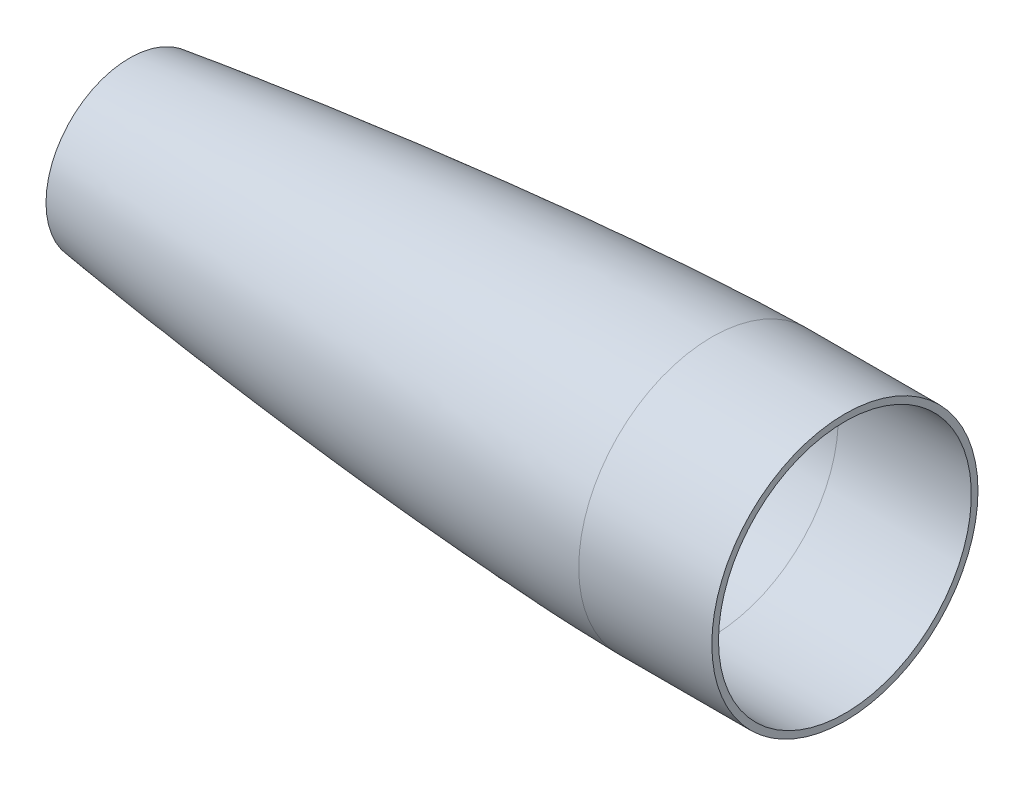
SolidWorks part; units mm, degrees
ref_plane "Front Plane" through (0, 0, 0) normal (0, 0, 1) x (1, 0, 0)
ref_plane "Top Plane" through (0, 0, 0) normal (0, 1, 0) x (1, 0, 0)
ref_plane "Right Plane" through (0, 0, 0) normal (1, 0, 0) x (0, 0, -1)
curve "Curve1"
  spline degree 3 poles (0, 0, 0) (0.3239, 0.2563, 0) (0.9404, 0.7441, 0) (1.9928, 1.2129, 0) (2.9928, 1.6503, 0) (3.9962, 2.0429, 0) (4.997, 2.4136, 0) (5.9977, 2.765, 0) (6.9982, 3.102, 0) (7.9985, 3.4266, 0) (8.9987, 3.7409, 0) (9.9989, 4.0463, 0) (10.999, 4.3437, 0) (11.9992, 4.6341, 0) (12.9993, 4.9182, 0) (13.9993, 5.1965, 0) (14.9994, 5.4695, 0) (15.9994, 5.7378, 0) (16.9995, 6.0015, 0) (17.9995, 6.261, 0) (18.9996, 6.5167, 0) (19.9996, 6.7687, 0) (20.9996, 7.0173, 0) (21.9996, 7.2626, 0) (22.9997, 7.5048, 0) (23.9997, 7.7441, 0) (24.9997, 7.9806, 0) (25.9997, 8.2145, 0) (26.9997, 8.4458, 0) (27.9997, 8.6747, 0) (28.9998, 8.9012, 0) (29.9998, 9.1256, 0) (30.9998, 9.3477, 0) (31.9998, 9.5678, 0) (32.9998, 9.7859, 0) (33.9998, 10.0021, 0) (34.9998, 10.2164, 0) (35.9998, 10.4289, 0) (36.9998, 10.6396, 0) (37.9998, 10.8486, 0) (38.9998, 11.056, 0) (39.9998, 11.2617, 0) (40.9999, 11.4659, 0) (41.9999, 11.6686, 0) (42.9999, 11.8698, 0) (43.9999, 12.0696, 0) (44.9999, 12.2679, 0) (45.9999, 12.4649, 0) (46.9999, 12.6605, 0) (47.9999, 12.8548, 0) (48.9999, 13.0478, 0) (49.9999, 13.2396, 0) (50.9999, 13.4301, 0) (51.9999, 13.6194, 0) (52.9999, 13.8076, 0) (53.9999, 13.9946, 0) (54.9999, 14.1804, 0) (55.9999, 14.3652, 0) (56.9999, 14.5488, 0) (57.9999, 14.7314, 0) (58.9999, 14.9129, 0) (59.9999, 15.0934, 0) (60.9999, 15.2728, 0) (61.9999, 15.4513, 0) (62.9999, 15.6288, 0) (63.9999, 15.8052, 0) (64.9999, 15.9808, 0) (65.9999, 16.1554, 0) (66.9999, 16.329, 0) (67.9999, 16.5018, 0) (68.9999, 16.6736, 0) (69.9999, 16.8445, 0) (70.9999, 17.0146, 0) (71.9999, 17.1838, 0) (72.9999, 17.3522, 0) (73.9999, 17.5197, 0) (74.9999, 17.6863, 0) (75.9999, 17.8522, 0) (76.9999, 18.0172, 0) (77.9999, 18.1814, 0) (78.9999, 18.3449, 0) (79.9999, 18.5075, 0) (80.9999, 18.6694, 0) (81.9999, 18.8305, 0) (82.9999, 18.9908, 0) (83.9999, 19.1504, 0) (84.9999, 19.3092, 0) (85.9999, 19.4673, 0) (86.9999, 19.6247, 0) (87.9999, 19.7814, 0) (88.9999, 19.9373, 0) (89.9999, 20.0925, 0) (90.9999, 20.2471, 0) (91.9999, 20.4009, 0) (92.9999, 20.554, 0) (93.9999, 20.7065, 0) (95, 20.8583, 0) (96, 21.0094, 0) (97, 21.1598, 0) (98, 21.3096, 0) (99, 21.4587, 0) (100, 21.6072, 0) (101, 21.755, 0) (102, 21.9022, 0) (103, 22.0488, 0) (104, 22.1947, 0) (105, 22.34, 0) (106, 22.4846, 0) (107, 22.6287, 0) (108, 22.7721, 0) (109, 22.915, 0) (110, 23.0572, 0) (111, 23.1988, 0) (112, 23.3398, 0) (113, 23.4803, 0) (114, 23.6201, 0) (115, 23.7594, 0) (116, 23.898, 0) (117, 24.0361, 0) (118, 24.1736, 0) (119, 24.3106, 0) (120, 24.4469, 0) (121, 24.5827, 0) (122, 24.718, 0) (123, 24.8526, 0) (124, 24.9867, 0) (125, 25.1203, 0) (126, 25.2533, 0) (127, 25.3857, 0) (128, 25.5176, 0) (129, 25.649, 0) (130, 25.7798, 0) (131, 25.91, 0) (132, 26.0397, 0) (133, 26.1689, 0) (134, 26.2975, 0) (135, 26.4257, 0) (136, 26.5532, 0) (137, 26.6803, 0) (138, 26.8068, 0) (139, 26.9328, 0) (140, 27.0582, 0) (141, 27.1832, 0) (142, 27.3076, 0) (143, 27.4315, 0) (144, 27.5549, 0) (145, 27.6777, 0) (146, 27.8001, 0) (147, 27.9219, 0) (148, 28.0432, 0) (149, 28.1641, 0) (150, 28.2844, 0) (151, 28.4041, 0) (152, 28.5234, 0) (153, 28.6422, 0) (154, 28.7605, 0) (155, 28.8782, 0) (156, 28.9955, 0) (157, 29.1122, 0) (158, 29.2285, 0) (159, 29.3442, 0) (160, 29.4595, 0) (161, 29.5742, 0) (162, 29.6885, 0) (163, 29.8022, 0) (164, 29.9155, 0) (165, 30.0282, 0) (166, 30.1405, 0) (167, 30.2522, 0) (168, 30.3635, 0) (169, 30.4743, 0) (170, 30.5845, 0) (171, 30.6943, 0) (172, 30.8036, 0) (173, 30.9124, 0) (174, 31.0207, 0) (175, 31.1285, 0) (176, 31.2358, 0) (177, 31.3426, 0) (178, 31.4489, 0) (179, 31.5547, 0) (180, 31.66, 0) (181, 31.7649, 0) (182, 31.8692, 0) (183, 31.973, 0) (184, 32.0764, 0) (185, 32.1792, 0) (186, 32.2816, 0) (187, 32.3834, 0) (188, 32.4848, 0) (189, 32.5856, 0) (190, 32.686, 0) (191, 32.7859, 0) (192, 32.8852, 0) (193, 32.9841, 0) (194, 33.0825, 0) (195, 33.1803, 0) (196, 33.2777, 0) (197, 33.3746, 0) (198, 33.4709, 0) (199, 33.5668, 0) (200, 33.6621, 0) (201, 33.757, 0) (202, 33.8513, 0) (203, 33.9451, 0) (204, 34.0385, 0) (205, 34.1313, 0) (206, 34.2236, 0) (207, 34.3153, 0) (208, 34.4066, 0) (209, 34.4973, 0) (210, 34.5876, 0) (211, 34.6773, 0) (212, 34.7665, 0) (213, 34.8551, 0) (214, 34.9433, 0) (215, 35.0309, 0) (216, 35.118, 0) (217, 35.2045, 0) (218, 35.2906, 0) (219, 35.3761, 0) (220, 35.461, 0) (221, 35.5454, 0) (222, 35.6293, 0) (223, 35.7126, 0) (224, 35.7954, 0) (225, 35.8776, 0) (226, 35.9593, 0) (227, 36.0404, 0) (228, 36.121, 0) (229, 36.201, 0) (230, 36.2805, 0) (231, 36.3594, 0) (232, 36.4377, 0) (233, 36.5154, 0) (234, 36.5926, 0) (235, 36.6692, 0) (236, 36.7452, 0) (237, 36.8206, 0) (238, 36.8954, 0) (239, 36.9696, 0) (240, 37.0432, 0) (241, 37.1163, 0) (242, 37.1887, 0) (243, 37.2605, 0) (244, 37.3317, 0) (245, 37.4022, 0) (246, 37.4722, 0) (247, 37.5415, 0) (248, 37.6102, 0) (249, 37.6782, 0) (250, 37.7455, 0) (251, 37.8123, 0) (252, 37.8783, 0) (253, 37.9437, 0) (254, 38.0084, 0) (255, 38.0725, 0) (256, 38.1358, 0) (257, 38.1985, 0) (258, 38.2604, 0) (259, 38.3216, 0) (260, 38.3821, 0) (261, 38.4419, 0) (262, 38.5009, 0) (263, 38.5592, 0) (264, 38.6168, 0) (265, 38.6735, 0) (266, 38.7295, 0) (267, 38.7847, 0) (268, 38.8391, 0) (269, 38.8926, 0) (270, 38.9454, 0) (271, 38.9972, 0) (272, 39.0483, 0) (273, 39.0984, 0) (274, 39.1477, 0) (275, 39.196, 0) (276, 39.2434, 0) (277, 39.2899, 0) (278, 39.3354, 0) (279, 39.3799, 0) (280, 39.4234, 0) (281, 39.4658, 0) (282, 39.5072, 0) (283, 39.5475, 0) (284, 39.5866, 0) (285, 39.6246, 0) (286, 39.6613, 0) (287, 39.6968, 0) (288, 39.731, 0) (289, 39.7638, 0) (290, 39.7952, 0) (291, 39.8251, 0) (292, 39.8533, 0) (293, 39.88, 0) (294, 39.9048, 0) (295, 39.9276, 0) (296, 39.9483, 0) (297, 39.9666, 0) (298, 39.982, 0) (299, 39.9947, 0) (299.6667, 39.9982, 0) (300, 40, 0) knots 0 0 0 0 0.004064 0.007736 0.011323 0.014865 0.018378 0.021871 0.025347 0.028811 0.032264 0.035709 0.039146 0.042576 0.046001 0.04942 0.052835 0.056246 0.059653 0.063056 0.066457 0.069854 0.073248 0.07664 0.08003 0.083417 0.086802 0.090186 0.093567 0.096946 0.100324 0.1037 0.107075 0.110448 0.11382 0.11719 0.120559 0.123927 0.127294 0.130659 0.134023 0.137387 0.140749 0.14411 0.14747 0.15083 0.154188 0.157546 0.160902 0.164258 0.167613 0.170968 0.174321 0.177674 0.181026 0.184378 0.187728 0.191078 0.194428 0.197776 0.201124 0.204472 0.207819 0.211165 0.214511 0.217856 0.221201 0.224545 0.227888 0.231231 0.234574 0.237916 0.241258 0.244599 0.247939 0.251279 0.254619 0.257958 0.261297 0.264636 0.267974 0.271311 0.274648 0.277985 0.281321 0.284657 0.287993 0.291328 0.294663 0.297997 0.301331 0.304665 0.307999 0.311332 0.314664 0.317997 0.321329 0.32466 0.327992 0.331323 0.334653 0.337984 0.341314 0.344643 0.347973 0.351302 0.354631 0.35796 0.361288 0.364616 0.367943 0.371271 0.374598 0.377925 0.381251 0.384578 0.387904 0.39123 0.394555 0.39788 0.401205 0.40453 0.407855 0.411179 0.414503 0.417827 0.42115 0.424474 0.427797 0.431119 0.434442 0.437764 0.441086 0.444408 0.44773 0.451051 0.454372 0.457693 0.461014 0.464335 0.467655 0.470975 0.474295 0.477615 0.480934 0.484253 0.487572 0.490891 0.49421 0.497528 0.500846 0.504165 0.507482 0.5108 0.514117 0.517435 0.520752 0.524068 0.527385 0.530702 0.534018 0.537334 0.54065 0.543965 0.547281 0.550596 0.553911 0.557226 0.560541 0.563856 0.56717 0.570484 0.573799 0.577112 0.580426 0.58374 0.587053 0.590366 0.593679 0.596992 0.600305 0.603617 0.606929 0.610242 0.613554 0.616865 0.620177 0.623489 0.6268 0.630111 0.633422 0.636733 0.640043 0.643354 0.646664 0.649974 0.653284 0.656594 0.659904 0.663213 0.666523 0.669832 0.673141 0.67645 0.679759 0.683067 0.686376 0.689684 0.692992 0.6963 0.699608 0.702916 0.706223 0.70953 0.712838 0.716145 0.719452 0.722758 0.726065 0.729371 0.732678 0.735984 0.73929 0.742596 0.745901 0.749207 0.752512 0.755817 0.759122 0.762427 0.765732 0.769037 0.772341 0.775646 0.77895 0.782254 0.785558 0.788862 0.792165 0.795469 0.798772 0.802075 0.805378 0.808681 0.811984 0.815287 0.818589 0.821891 0.825193 0.828496 0.831797 0.835099 0.838401 0.841702 0.845003 0.848305 0.851606 0.854907 0.858207 0.861508 0.864808 0.868109 0.871409 0.874709 0.878009 0.881308 0.884608 0.887907 0.891207 0.894506 0.897805 0.901104 0.904402 0.907701 0.910999 0.914297 0.917596 0.920894 0.924191 0.927489 0.930787 0.934084 0.937381 0.940678 0.943975 0.947272 0.950569 0.953865 0.957161 0.960458 0.963754 0.96705 0.970345 0.973641 0.976936 0.980232 0.983527 0.986822 0.990117 0.993411 0.996706 1 1 1 1
sketch "Sketch2" plane through (0, 0, 0) normal (0, 0, 1) x (1, 0, 0)
  line L0 (0, 0) -> (129.646, 0) construction
  line L2 (300, 40) -> (300.0106, 38) construction
  line L3 (0, 0) -> (4.2671, 0)
  line L4 (300, 40) -> (340, 40)
  line L5 (340, 40) -> (340, 38)
  line L6 (340, 38) -> (300.0106, 38)
  line L7 (125, 25.1202) -> (125, 0)
  line L8 (125, 0) -> (127, 0)
  line L9 (127, 0) -> (127, 23.3682)
  spline S0 degree 3 poles (-1605.8079, 2533.2499) (16.7759, -86.5021) (-13.4623, -5.6713) (1.9928, 1.2129) (2.9928, 1.6503) (3.9962, 2.0429) (4.997, 2.4136) (5.9977, 2.765) (6.9982, 3.102) (7.9985, 3.4266) (8.9987, 3.7409) (9.9989, 4.0463) (10.999, 4.3437) (11.9992, 4.6341) (12.9993, 4.9182) (13.9993, 5.1965) (14.9994, 5.4695) (15.9994, 5.7378) (17.3322, 6.0892) (18.9983, 6.5182) (20.9985, 7.0186) (22.9987, 7.506) (24.9988, 7.9817) (26.9989, 8.4468) (28.999, 8.9022) (31.332, 9.4229) (33.9983, 10.0043) (36.9985, 10.6416) (39.9986, 11.2636) (42.9987, 11.8715) (46.3318, 12.5325) (49.9982, 13.2423) (53.9984, 13.9971) (57.9985, 14.7338) (62.3316, 15.5134) (66.9981, 16.3324) (71.9982, 17.187) (77.3314, 18.0757) (82.9979, 18.9949) (88.9981, 19.9411) (95.3312, 20.913) (101.9978, 21.907) (108.9979, 22.9195) (116.3311, 23.9492) (123.9977, 24.9923) (131.9978, 26.0451) (140.331, 27.1059) (148.9975, 28.1706) (157.9977, 29.2349) (166.9978, 30.2586) (175.9979, 31.2421) (184.998, 32.1856) (193.998, 33.089) (202.665, 33.9198) (210.9985, 34.6826) (218.6654, 35.3525) (225.9989, 35.9637) (232.9989, 36.5199) (239.6657, 37.0229) (245.9992, 37.4758) (251.666, 37.8596) (256.9995, 38.2012) (261.6662, 38.4837) (265.9996, 38.7315) (269.9996, 38.9474) (273.6664, 39.1331) (276.9998, 39.2912) (279.9998, 39.4248) (282.6665, 39.5352) (284.9999, 39.6252) (286.9999, 39.6975) (288.9999, 39.7645) (290.6666, 39.8156) (292.3333, 39.8628) (293.6666, 39.8971) (295, 39.9276) (296, 39.9483) (297, 39.9666) (298, 39.982) (343.7491, 40.5639) (389.362, 18.16) (408.5654, 3036.1615) knots -0.154953 -0.154953 -0.154953 -0.154953 0.004064 0.007736 0.011323 0.014865 0.018378 0.021871 0.025347 0.028811 0.032264 0.035709 0.039146 0.042576 0.046001 0.04942 0.052835 0.056246 0.059653 0.066457 0.073248 0.08003 0.086802 0.093567 0.100324 0.107075 0.11719 0.127294 0.137387 0.14747 0.157546 0.170968 0.184378 0.197776 0.211165 0.227888 0.244599 0.261297 0.281321 0.301331 0.321329 0.344643 0.367943 0.39123 0.417827 0.444408 0.470975 0.500846 0.530702 0.560541 0.590366 0.620177 0.649974 0.679759 0.706223 0.732678 0.755817 0.77895 0.802075 0.821891 0.841702 0.858207 0.874709 0.887907 0.901104 0.914297 0.924191 0.934084 0.943975 0.950569 0.957161 0.963754 0.970345 0.973641 0.980232 0.983527 0.986822 0.990117 0.993411 0.996706 1.44228 1.44228 1.44228 1.44228 only from (0, 0) to (300, 40) construction
  spline S1 degree 3 poles (0, 0) (0.3239, 0.2563) (0.9404, 0.7441) (1.9928, 1.2129) (2.9928, 1.6503) (3.9962, 2.0429) (4.997, 2.4136) (5.9977, 2.765) (6.9982, 3.102) (7.9985, 3.4266) (8.9987, 3.7409) (9.9989, 4.0463) (10.999, 4.3437) (11.9992, 4.6341) (12.9993, 4.9182) (13.9993, 5.1965) (14.9994, 5.4695) (15.9994, 5.7378) (17.3322, 6.0892) (18.9983, 6.5182) (20.9985, 7.0186) (22.9987, 7.506) (24.9988, 7.9817) (26.9989, 8.4468) (28.999, 8.9022) (31.332, 9.4229) (33.9983, 10.0043) (36.9985, 10.6416) (39.9986, 11.2636) (42.9987, 11.8715) (46.3318, 12.5325) (49.9982, 13.2423) (53.9984, 13.9971) (57.9985, 14.7338) (62.3316, 15.5134) (66.9981, 16.3324) (71.9982, 17.187) (77.3314, 18.0757) (82.9979, 18.9949) (88.9981, 19.9411) (95.3312, 20.913) (101.9978, 21.907) (108.9979, 22.9195) (116.3311, 23.9492) (123.9977, 24.9923) (131.9978, 26.0451) (140.331, 27.1059) (148.9975, 28.1706) (157.9977, 29.2349) (166.9978, 30.2586) (175.9979, 31.2421) (184.998, 32.1856) (193.998, 33.089) (202.665, 33.9198) (210.9985, 34.6826) (218.6654, 35.3525) (225.9989, 35.9637) (232.9989, 36.5199) (239.6657, 37.0229) (245.9992, 37.4758) (251.666, 37.8596) (256.9995, 38.2012) (261.6662, 38.4837) (265.9996, 38.7315) (269.9996, 38.9474) (273.6664, 39.1331) (276.9998, 39.2912) (279.9998, 39.4248) (282.6665, 39.5352) (284.9999, 39.6252) (286.9999, 39.6975) (288.9999, 39.7645) (290.6666, 39.8156) (292.3333, 39.8628) (293.6666, 39.8971) (295, 39.9276) (296, 39.9483) (297, 39.9666) (298, 39.982) (299, 39.9947) (299.6667, 39.9982) (300, 40) knots 0 0 0 0 0.004064 0.007736 0.011323 0.014865 0.018378 0.021871 0.025347 0.028811 0.032264 0.035709 0.039146 0.042576 0.046001 0.04942 0.052835 0.056246 0.059653 0.066457 0.073248 0.08003 0.086802 0.093567 0.100324 0.107075 0.11719 0.127294 0.137387 0.14747 0.157546 0.170968 0.184378 0.197776 0.211165 0.227888 0.244599 0.261297 0.281321 0.301331 0.321329 0.344643 0.367943 0.39123 0.417827 0.444408 0.470975 0.500846 0.530702 0.560541 0.590366 0.620177 0.649974 0.679759 0.706223 0.732678 0.755817 0.77895 0.802075 0.821891 0.841702 0.858207 0.874709 0.887907 0.901104 0.914297 0.924191 0.934084 0.943975 0.950569 0.957161 0.963754 0.970345 0.973641 0.980232 0.983527 0.986822 0.990117 0.993411 0.996706 1 1 1 1
  spline S2 degree 1 poles (1.241, -1.5684) (300.0106, 38) knots 0 0 1 1 construction
  spline S3 degree 3 poles (1.241, -1.5684) (1.3807, -1.4578) (1.6881, -1.216) (1.9997, -1.0018) (2.3173, -0.8331) (2.8232, -0.6074) (3.3618, -0.3714) (3.7849, -0.1929) (4.1325, -0.0528) (4.4813, 0.0842) (5.4558, 0.4556) (7.0834, 1.031) (10.037, 1.984) (13.7867, 3.0797) (18.3317, 4.2942) (22.9057, 5.4346) (29.0314, 6.8774) (36.7255, 8.5622) (45.9958, 10.445) (55.293, 12.2166) (64.6107, 13.8956) (77.0563, 16.0277) (92.6469, 18.5165) (108.7755, 20.885) (121.7966, 22.6819) (134.3222, 24.3389) (155.7568, 27.0201) (186.6476, 30.4535) (218.1037, 33.3675) (243.2964, 35.3133) (262.2047, 36.5525) (277.9645, 37.3696) (290.5821, 37.831) (296.865, 37.9834) (300.0106, 38) knots 0 0 0 0 0.001953 0.003906 0.005859 0.007812 0.009766 0.011719 0.012737 0.013714 0.015625 0.023438 0.03125 0.046875 0.0625 0.078125 0.09375 0.125 0.15625 0.1875 0.21875 0.25 0.3125 0.375 0.4113 0.44255 0.5 0.625 0.75 0.8125 0.875 0.9375 0.96875 1 1 1 1 only from (4.2671, 0) to (300.0106, 38)
  dimension "D2" = 40
  dimension "D3" = 2
  dimension "D4" = 175
  dimension "D1" = 2
revolve "Revolve1" add sketch "Sketch2" angle 360 about L0
sketch "Sketch3" plane through (125, 0, 0) normal (-1, 0, 0) x (0, 0, 1)
  circle A2 centre (0, 0) radius 3.1
  dimension "D1" = 6.2
extrude "Cut-Extrude1" cut sketch "Sketch3" against normal through all
